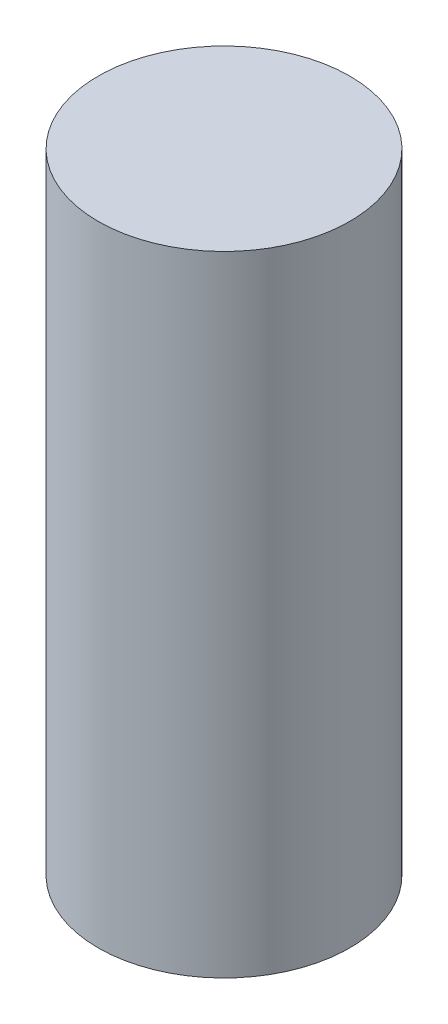
SolidWorks part; units mm, degrees
ref_plane "前视基准面" through (0, 0, 0) normal (0, 0, 1) x (1, 0, 0)
ref_plane "上视基准面" through (0, 0, 0) normal (0, 1, 0) x (1, 0, 0)
ref_plane "右视基准面" through (0, 0, 0) normal (1, 0, 0) x (0, 0, -1)
other "Configuration Table"
sketch "草图1" plane through (0, 0, 0) normal (0, 1, 0) x (1, 0, 0)
  circle A0 centre (0, 0) radius 300
  dimension "D1" = 600
extrude "凸台-拉伸1" add sketch "草图1" along normal blind 1500
